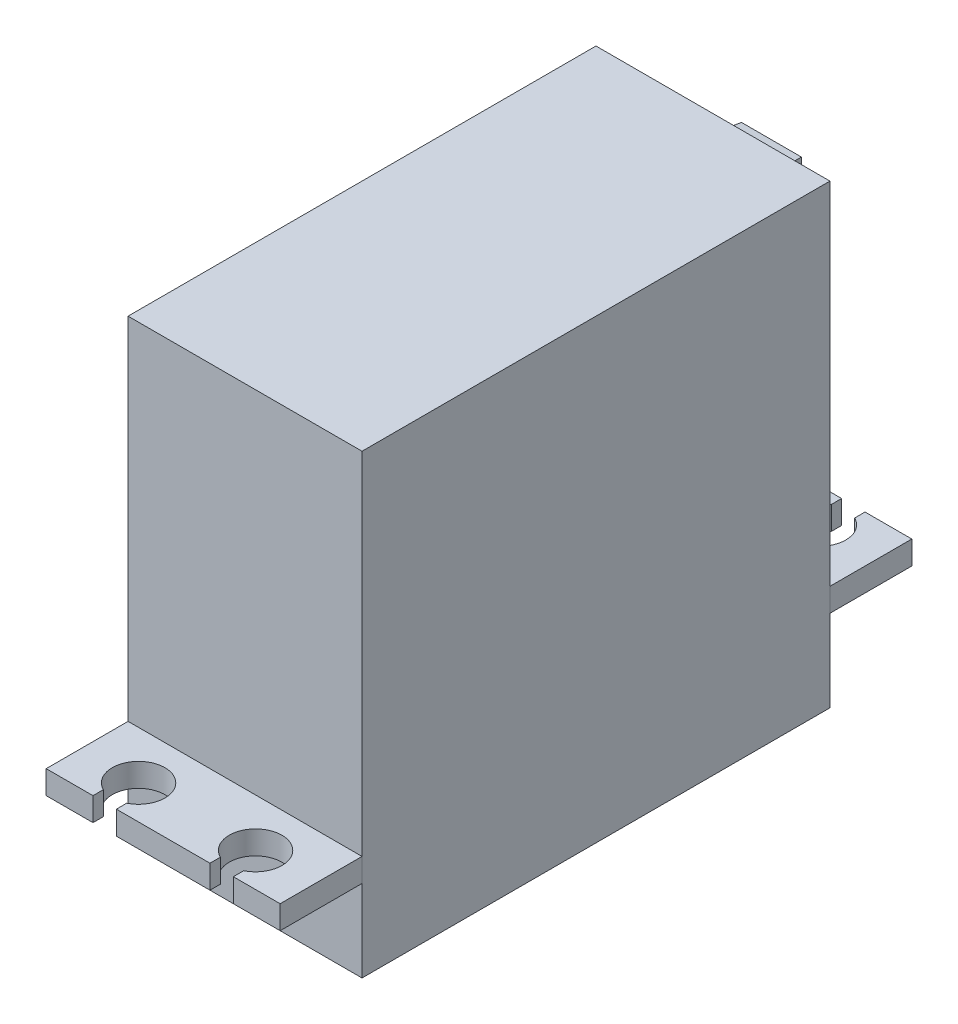
SolidWorks part; units mm, degrees
ref_plane "前视基准面" through (0, 0, 0) normal (0, 0, 1) x (1, 0, 0)
ref_plane "上视基准面" through (0, 0, 0) normal (0, 1, 0) x (1, 0, 0)
ref_plane "右视基准面" through (0, 0, 0) normal (1, 0, 0) x (0, 0, -1)
sketch "草图1" plane through (0, 0, 0) normal (0, 1, 0) x (1, 0, 0)
  line L1 (-10, 20) -> (10, 20)
  line L2 (-10, 20) -> (-10, -20)
  line L3 (-10, -20) -> (10, -20)
  line L4 (10, 20) -> (10, -20)
  line L5 (-10, 20) -> (10, -20) construction
  line L6 (-10, -20) -> (10, 20) construction
  point P0 (0, 0)
  dimension "D1" = 20
  dimension "D2" = 40
extrude "凸台-拉伸1" add sketch "草图1" along normal blind 39
sketch "草图2" plane through (0, 0, 0) normal (0, -1, 0) x (1, 0, 0)
  line L0 (10, -20) -> (-10, -20) construction
  circle A0 centre (0, -10) radius 6.5
  dimension "D1" = 13
  dimension "D2" = 10
extrude "凸台-拉伸2" add sketch "草图2" along normal blind 2.1
sketch "草图3" plane through (0, -2.1, 0) normal (0, -1, 0) x (1, 0, 0)
  circle A0 centre (0, -10) radius 2.9
  dimension "D1" = 5.8
extrude "凸台-拉伸3" add sketch "草图3" along normal blind 3.5
sketch "草图4" plane through (0, 0, -20) normal (0, 0, -1) x (-1, 0, 0)
  line L0 (-10, 39) -> (10, 39) construction
  line L1 (3, 32) -> (-3, 32)
  line L2 (3, 32) -> (3, 35)
  line L3 (3, 35) -> (-3, 35)
  line L4 (-3, 32) -> (-3, 35)
  point P4 (0, 32)
  dimension "D1" = 3
  dimension "D2" = 4
  dimension "D3" = 6
extrude "凸台-拉伸4" add sketch "草图4" along normal blind 5 draft 5
ref_plane "基准面1" through (0, 8, 0) normal (0, -1, 0) x (-1, 0, 0)
sketch "草图5" plane through (0, 8, 0) normal (0, -1, 0) x (-1, 0, 0)
  line L0 (-10, -20) -> (-10, 20) construction
  line L1 (-10, -20) -> (10, -20)
  line L2 (-10, -20) -> (-10, -27)
  line L3 (-10, -27) -> (-6, -27)
  line L4 (10, -20) -> (10, -27)
  line L5 (-10, 20) -> (10, 20)
  line L6 (-10, 20) -> (-10, 27)
  line L7 (-10, 27) -> (-6, 27)
  line L8 (10, 20) -> (10, 27)
  line L9 (-6, -26.1156) -> (-6, -27)
  line L10 (-4, -26.1156) -> (-4, -27)
  line L11 (-10, 0) -> (10, 0) construction
  line L12 (10, 20) -> (10, -20) construction
  line L13 (0, -20.4) -> (0, 20) construction
  line L16 (-4, 26.1156) -> (-4, 27)
  line L17 (-6, 26.1156) -> (-6, 27)
  line L18 (4, 26.1156) -> (4, 27)
  line L19 (6, 26.1156) -> (6, 27)
  line L20 (4, -26.1156) -> (4, -27)
  line L21 (6, -26.1156) -> (6, -27)
  line L22 (-4, -27) -> (4, -27)
  line L23 (6, -27) -> (10, -27)
  line L24 (-4, 27) -> (4, 27)
  line L25 (6, 27) -> (10, 27)
  arc A0 (-4, -26.1156) -> (-6, -26.1156) centre (-5, -24.1) ccw
  arc A1 (6, -26.1156) -> (4, -26.1156) centre (5, -24.1) ccw
  arc A2 (-6, 26.1156) -> (-4, 26.1156) centre (-5, 24.1) ccw
  arc A3 (4, 26.1156) -> (6, 26.1156) centre (5, 24.1) ccw
  dimension "D3" = 4.5
  dimension "D4" = 10
  dimension "D5" = 5
  dimension "D6" = 24.1
  dimension "D1" = 54
  dimension "D2" = 7
extrude "凸台-拉伸5" add sketch "草图5" along normal blind 1 and the other way blind 1 separate body
